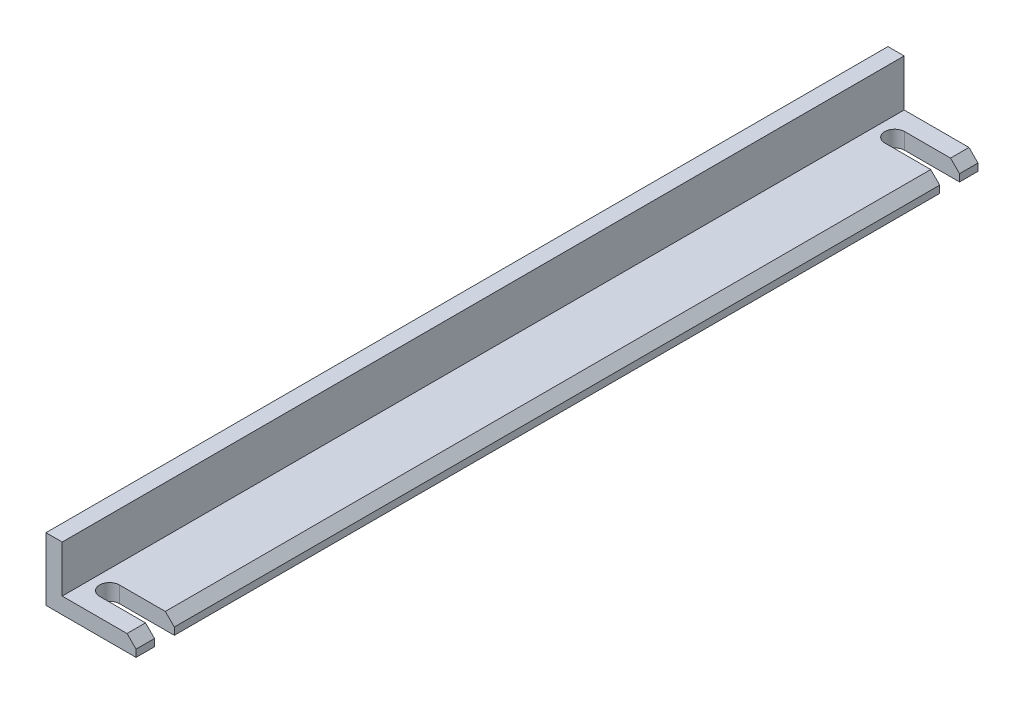
SolidWorks part; units mm, degrees
material " 40Х13 ГОСТ 4543-71"
ref_plane "Спереди" through (0, 0, 0) normal (0, 0, 1) x (1, 0, 0)
ref_plane "Сверху" through (0, 0, 0) normal (0, 1, 0) x (1, 0, 0)
ref_plane "Справа" through (0, 0, 0) normal (1, 0, 0) x (0, 0, -1)
sketch "Sketch1" plane through (0, 0, 0) normal (0, 0, 1) x (1, 0, 0)
  line L0 (0, 0) -> (0, 7)
  line L1 (0, 0) -> (10, 0)
  dimension "D1" = 10
  dimension "D2" = 7
extrude "Extrude-Thin1" add sketch "Sketch1" along normal mid plane 93.5 thin
chamfer "Chamfer1" distance 1 angle 45 1 edges at (10, 1.8, 0)
sketch "Sketch2" plane through (0, 1.8, 0) normal (0, 1, 0) x (1, 0, 0)
  line L0 (11.5225, -43.6) -> (3.9, -43.6) construction
  line L1 (11.5225, -44.7) -> (3.9, -44.7)
  line L2 (11.5225, -42.5) -> (3.9, -42.5)
  line L4 (1.8, -46.75) -> (1.8, 46.75) construction
  arc A0 (11.5225, -44.7) -> (11.5225, -42.5) centre (11.5225, -43.6) ccw
  arc A1 (3.9, -42.5) -> (3.9, -44.7) centre (3.9, -43.6) ccw
  point P2 (7.7113, -43.6)
  dimension "D3" = 1
  dimension "D1" = 2.2
  dimension "D2" = 42.5
extrude "Cut-Extrude1" cut sketch "Sketch2" against normal blind 10
mirror "Mirror1" about plane through (0, 0, 0) normal (0, 0, 1) of "Cut-Extrude1"
